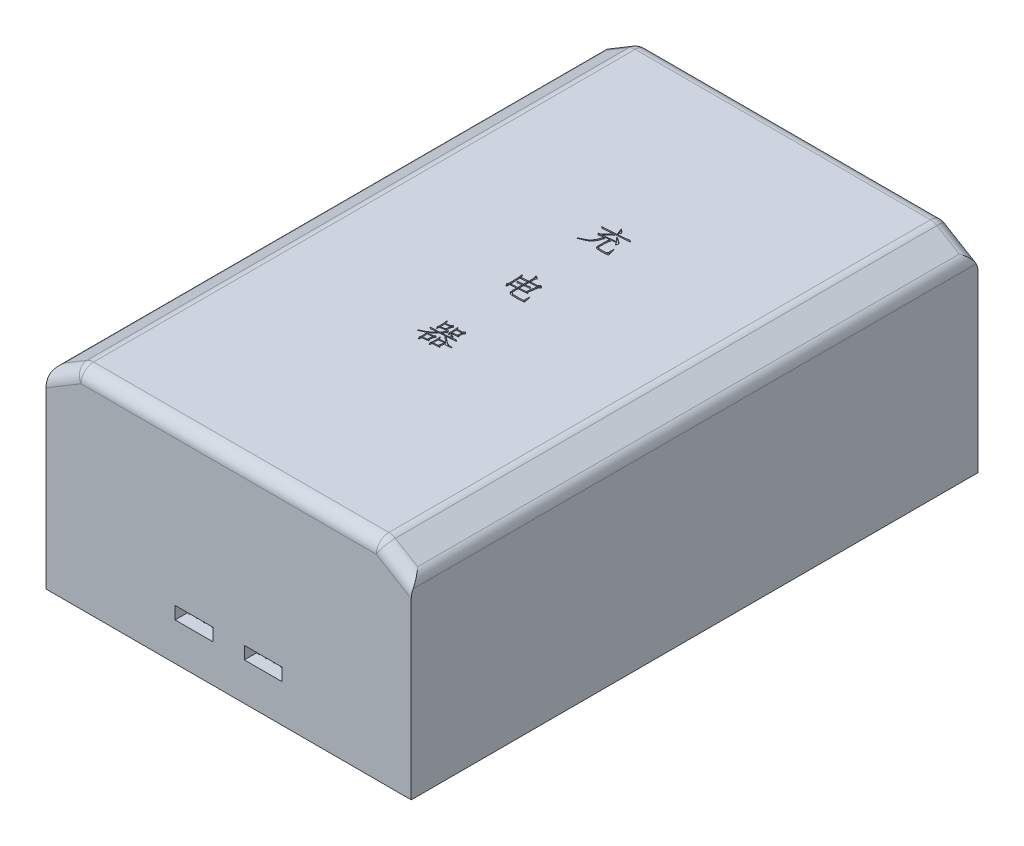
SolidWorks part; units mm, degrees
ref_plane "前视基准面" through (0, 0, 0) normal (0, 0, 1) x (1, 0, 0)
ref_plane "上视基准面" through (0, 0, 0) normal (0, 1, 0) x (1, 0, 0)
ref_plane "右视基准面" through (0, 0, 0) normal (1, 0, 0) x (0, 0, -1)
other "Configuration Table"
sketch "草图1" plane through (0, 0, 0) normal (0, 1, 0) x (1, 0, 0)
  line L1 (0, 0) -> (-58, 0)
  line L2 (0, 0) -> (0, 90)
  line L3 (0, 90) -> (-58, 90)
  line L4 (-58, 0) -> (-58, 90)
  dimension "D1" = 58
  dimension "D2" = 90
extrude "凸台-拉伸1" add sketch "草图1" along normal blind 33
sketch "草图2" plane through (0, 0, 0) normal (0, 0, 1) x (1, 0, 0)
  line L0 (-53, 33) -> (-58, 30)
  line L1 (-58, 33) -> (0, 33) construction
  line L2 (-58, 33) -> (-58, 0) construction
  line L3 (-58, 30) -> (-58, 33)
  line L4 (-58, 33) -> (-53, 33)
  line L5 (-29, 33) -> (-29, 22.8947) construction
  line L6 (0, 30) -> (0, 33)
  line L7 (-5, 33) -> (0, 30)
  line L8 (0, 33) -> (-5, 33)
  dimension "D1" = 5
  dimension "D2" = 3
extrude "切除-拉伸1" cut sketch "草图2" against normal through all
fillet "圆角1" radius 2 10 edges at (-55.5, 31.5, 0) (-2.5, 31.5, 0) (0, 30, -45) (-5, 33, -45) (-58, 30, -45) (-53, 33, -45) (-55.5, 31.5, -90) (-2.5, 31.5, -90) (-29, 33, -90) (-29, 33, 0)
sketch "草图3" plane through (0, 33, 0) normal (0, 1, 0) x (1, 0, 0)
  text T0 "充\r\n\r\n电\r\n\r\n器" font "汉仪长仿宋体" height 3.5
extrude "切除-拉伸2" cut sketch "草图3" against normal blind 0.2
sketch "草图4" plane through (0, 0, 0) normal (0, 0, 1) x (1, 0, 0)
  line L0 (-58, 27.6676) -> (-58, 0) construction
  line L1 (-37.5, 8) -> (-31.5, 8)
  line L2 (-37.5, 8) -> (-37.5, 6)
  line L3 (-37.5, 6) -> (-31.5, 6)
  line L4 (-31.5, 8) -> (-31.5, 6)
  line L5 (-26.5, 8) -> (-20.5, 8)
  line L6 (-26.5, 8) -> (-26.5, 6)
  line L7 (-26.5, 6) -> (-20.5, 6)
  line L8 (-20.5, 8) -> (-20.5, 6)
  line L10 (-58, 0) -> (0, 0) construction
  dimension "D1" = 6
  dimension "D2" = 6
  dimension "D3" = 5
  dimension "D4" = 2
  dimension "D5" = 2
  dimension "D6" = 20.5
  dimension "D7" = 6
  dimension "D8" = 6
extrude "切除-拉伸3" cut sketch "草图4" against normal blind 6
sketch "草图5" plane through (0, 0, -6) normal (0, 0, 1) x (1, 0, 0)
  line L0 (-37.5, 7) -> (-20.5, 7) construction
  line L1 (-37.5, 8) -> (-37.5, 6) construction
  line L2 (-20.5, 6) -> (-20.5, 8) construction
  line L4 (-37.5, 8) -> (-37.5, 6) construction
  line L5 (-31.5, 6) -> (-31.5, 8) construction
  line L6 (-26.5, 8) -> (-26.5, 6) construction
  circle A0 centre (-36.3, 7) radius 0.15
  circle A1 centre (-35.1, 7) radius 0.15
  circle A2 centre (-33.9, 7) radius 0.15
  circle A3 centre (-32.7, 7) radius 0.15
  circle A4 centre (-25.3, 7) radius 0.15
  circle A5 centre (-24.1, 7) radius 0.15
  circle A6 centre (-22.9, 7) radius 0.15
  circle A7 centre (-21.7, 7) radius 0.15
  dimension "D1" = 1.2
  dimension "D2" = 1.2
  dimension "D3" = 1.2
  dimension "D4" = 1.2
  dimension "D5" = 1.2
  dimension "D6" = 1.2
  dimension "D7" = 1.2
  dimension "D8" = 1.2
  dimension "D9" = 0.3
extrude "凸台-拉伸2" add sketch "草图5" along normal blind 5
fillet "圆角2" radius 0.1 8 edges at (-21.55, 7, -1) (-22.75, 7, -1) (-23.95, 7, -1) (-25.15, 7, -1) (-32.55, 7, -1) (-33.75, 7, -1) (-34.95, 7, -1) (-36.15, 7, -1)
sketch "草图6" plane through (0, 0, -90) normal (0, 0, -1) x (-1, 0, 0)
  line L1 (22, 9) -> (36, 9)
  line L3 (22, 5) -> (36, 5)
  line L5 (21.0588, 8.7647) -> (36.9412, 5.2353) construction
  line L6 (21.0588, 5.2353) -> (36.9412, 8.7647) construction
  line L8 (0, 0) -> (58, 0) construction
  line L9 (29, 7) -> (29, 13.8699) construction
  arc A0 (22, 9) -> (22, 5) centre (22, 7) ccw
  arc A1 (36, 9) -> (36, 5) centre (36, 7) cw
  point P0 (29, 7)
  dimension "D3" = 4
  dimension "D4" = 5
  dimension "D5" = 7
extrude "切除-拉伸4" cut sketch "草图6" against normal blind 5
